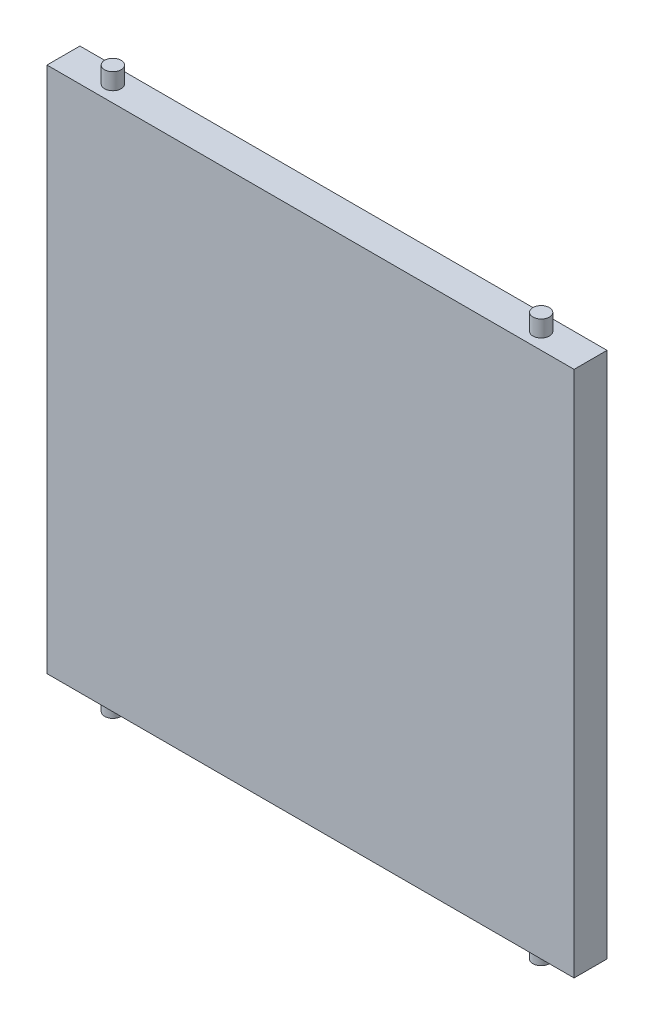
SolidWorks part; units mm, degrees
ref_plane "前视基准面" through (0, 0, 0) normal (0, 0, 1) x (1, 0, 0)
ref_plane "上视基准面" through (0, 0, 0) normal (0, 1, 0) x (1, 0, 0)
ref_plane "右视基准面" through (0, 0, 0) normal (1, 0, 0) x (0, 0, -1)
sketch "草图2" plane through (0, 0, 0) normal (0, 0, 1) x (1, 0, 0)
  line L1 (-80, -80) -> (80, -80)
  line L2 (-80, -80) -> (-80, 80)
  line L3 (-80, 80) -> (80, 80)
  line L4 (80, -80) -> (80, 80)
  line L5 (-80, -80) -> (80, 80) construction
  line L6 (-80, 80) -> (80, -80) construction
  point P0 (0, 0)
  dimension "D1" = 160
extrude "凸台-拉伸1" add sketch "草图2" along normal blind 10
sketch "草图4" plane through (0, 0, 0) normal (0, 1, 0) x (1, 0, 0)
  line L0 (0, 0) -> (0, -10) construction
  line L1 (80, -10) -> (-80, -10) construction
  line L2 (-80, -10) -> (-80, 0) construction
  circle A0 centre (-65, -5) radius 2.5
  circle A2 centre (65, -5) radius 2.5
  dimension "D1" = 5
  dimension "D2" = 15
extrude "凸台-拉伸2" add sketch "草图4" along normal mid plane 170
